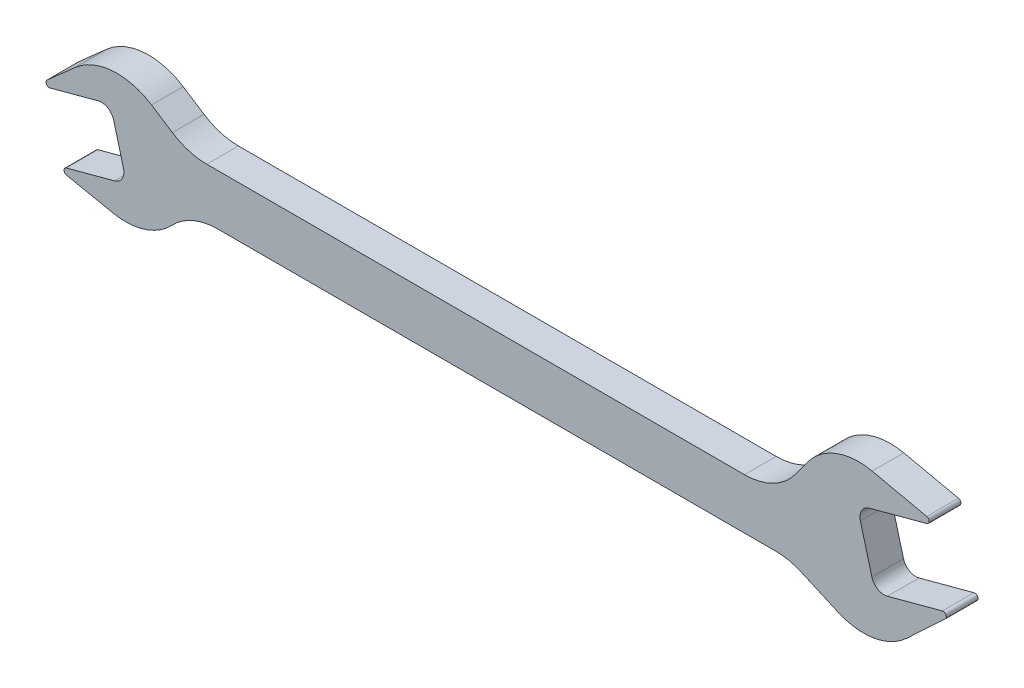
SolidWorks part; units mm, degrees
material "V2a"
ref_plane "Vorne" through (0, 0, 0) normal (0, 0, 1) x (1, 0, 0)
ref_plane "Oben" through (0, 0, 0) normal (0, 1, 0) x (1, 0, 0)
ref_plane "Rechts" through (0, 0, 0) normal (1, 0, 0) x (0, 0, -1)
sketch "Skizze1" plane through (0, 0, 0) normal (0, 0, 1) x (1, 0, 0)
  line L0 (0, 0) -> (46.6523, 0) construction
  line L1 (46.5129, 2.5) -> (55.2112, 14.4703)
  line L2 (-46.5129, -5.5) -> (48.4741, -5.5)
  line L3 (-57.4972, -1.7238) -> (-28.2451, 6.1143) construction
  line L4 (-46.5129, 2.5) -> (46.5129, 2.5)
  line L5 (60.6371, 1.9479) -> (167.5349, 30.5911) construction
  line L7 (-46.5129, 2.5) -> (-58.6711, 10.3849)
  line L8 (55.2112, 14.4703) -> (72.2228, 10.7463)
  line L9 (72.2228, 10.7463) -> (59.2136, 7.2605)
  line L10 (59.2136, 7.2605) -> (62.0606, -3.3646)
  line L11 (62.0606, -3.3646) -> (74.6176, 0)
  line L12 (74.6176, 0) -> (62.1993, -11.6097)
  line L13 (62.1993, -11.6097) -> (48.4741, -5.5)
  line L14 (-58.6711, 10.3849) -> (-70.3824, 0)
  line L15 (-70.3824, 0) -> (-58.7913, 3.1058)
  line L16 (-58.7913, 3.1058) -> (-56.2031, -6.5534)
  line L17 (-56.2031, -6.5534) -> (-67.7942, -9.6593)
  line L18 (-67.7942, -9.6593) -> (-52.4595, -12.7973)
  line L19 (-52.4595, -12.7973) -> (-46.5129, -5.5)
  point P3 (0, 0)
  point P8 (60.6371, 1.9479)
  point P31 (0, 2.5)
  point P34 (-46.5129, -5.5)
  point P37 (-46.5129, 2.5)
  dimension "D5" = 2.5
  dimension "D9" = 24
  dimension "D1" = 15
  dimension "D2" = 11
  dimension "D3" = 15
  dimension "D4" = 27
  dimension "D6" = 10
  dimension "D7" = 145
  dimension "D8" = 8
  dimension "D10" = 24
  dimension "D11" = 27
  dimension "D12" = 2
  dimension "D13" = 2
  dimension "D14" = 12
  dimension "D15" = 13
  dimension "D16" = 13.5
extrude "Aufsatz-Linear austragen1" add sketch "Skizze1" along normal mid plane 5
fillet "Verrundung1" radius 10 2 edges at (-52.4595, -12.7973, 0) (-58.6711, 10.3849, 0)
fillet "Verrundung2" radius 10 2 edges at (62.1993, -11.6097, 0) (55.2112, 14.4703, 0)
fillet "Verrundung3" radius 2 4 edges at (62.0606, -3.3646, 0) (59.2136, 7.2605, 0) (-56.2031, -6.5534, 0) (-58.7913, 3.1058, 0)
fillet "Verrundung4" radius 0.5 4 edges at (74.6176, 0, 0) (72.2228, 10.7463, 0) (-67.7942, -9.6593, 0) (-70.3824, 0, 0)
fillet "Verrundung5" radius 10 4 edges at (46.5129, 2.5, 0) (48.4741, -5.5, 0) (-46.5129, -5.5, 0) (-46.5129, 2.5, 0)
